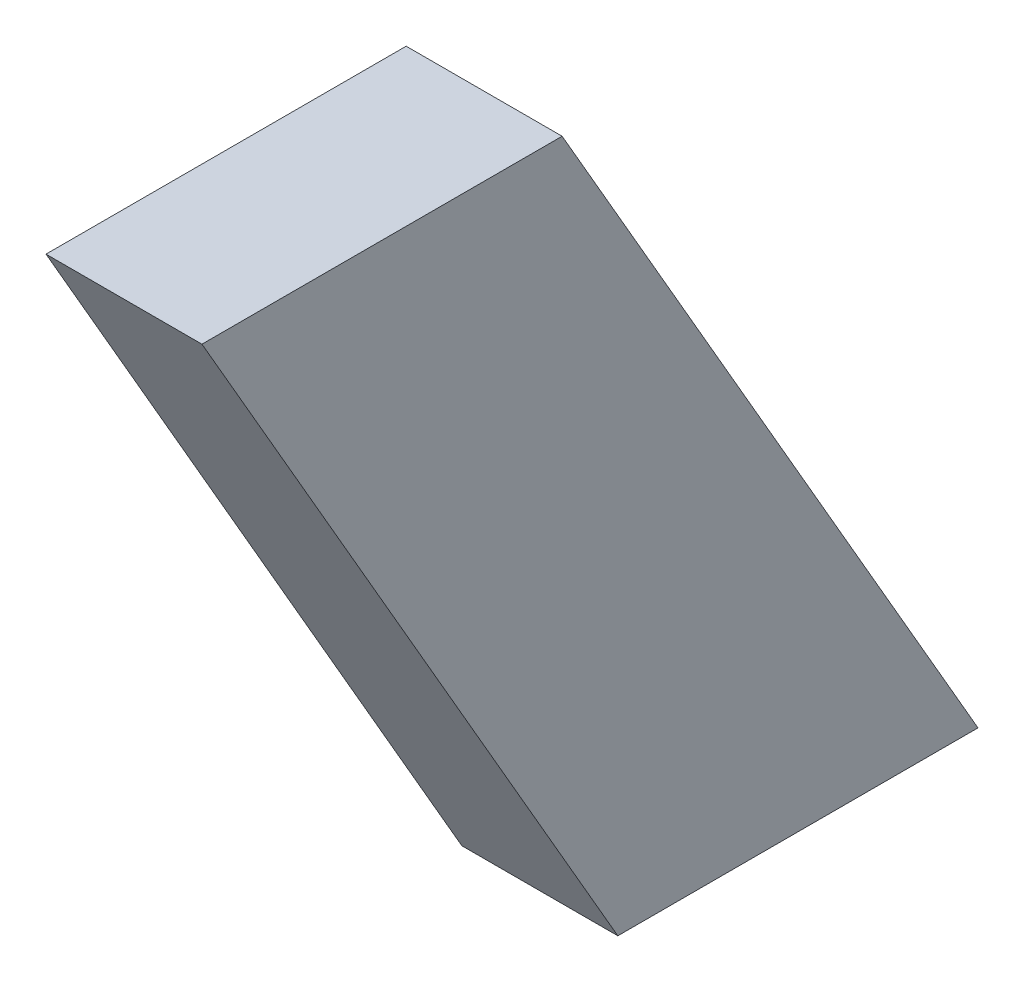
SolidWorks part; units mm, degrees
ref_plane "Front Plane" through (0, 0, 0) normal (0, 0, 1) x (1, 0, 0)
ref_plane "Top Plane" through (0, 0, 0) normal (0, 1, 0) x (1, 0, 0)
ref_plane "Right Plane" through (0, 0, 0) normal (1, 0, 0) x (0, 0, -1)
sketch "Sketch2" plane through (0, 0, 0) normal (1, 0, 0) x (0, 0, -1)
  line L0 (0, 0) -> (43.9941, 0)
  line L1 (43.9941, 0) -> (94.7941, -87.9882)
  line L2 (94.7941, -87.9882) -> (50.8, -87.9882)
  line L3 (50.8, -87.9882) -> (0, 0)
  dimension "D1" = 60
  dimension "D2" = 38.1
  dimension "D3" = 101.6
extrude "Boss-Extrude1" add sketch "Sketch2" along normal blind 19.05
